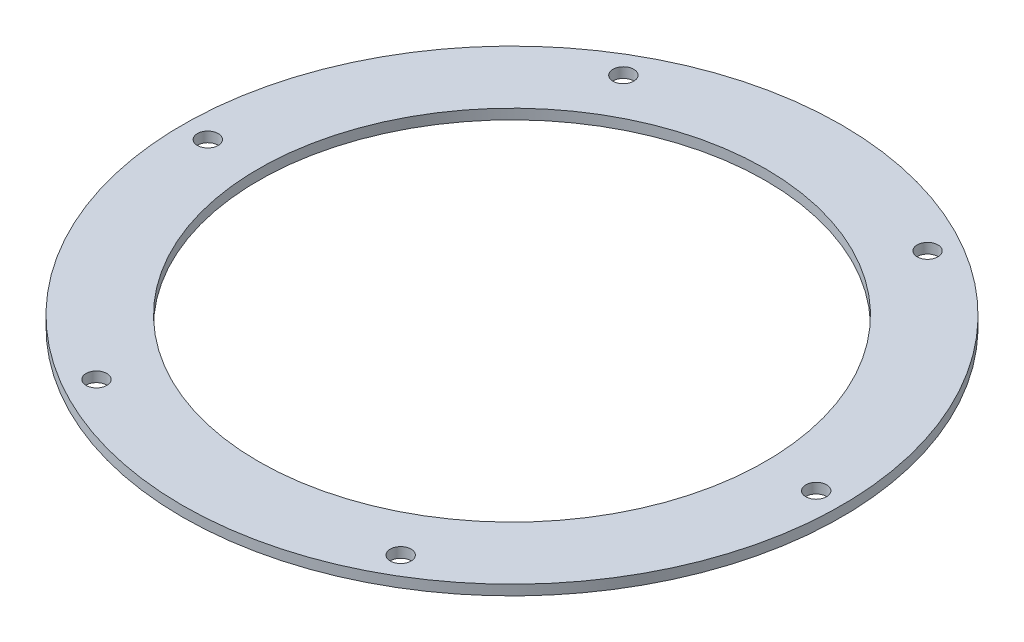
SolidWorks part; units mm, degrees
ref_plane "前视基准面" through (0, 0, 0) normal (0, 0, 1) x (1, 0, 0)
ref_plane "上视基准面" through (0, 0, 0) normal (0, 1, 0) x (1, 0, 0)
ref_plane "右视基准面" through (0, 0, 0) normal (1, 0, 0) x (0, 0, -1)
sketch "草图1" plane through (0, 0, 0) normal (0, 1, 0) x (1, 0, 0)
  circle A0 centre (0, 0) radius 50
  circle A1 centre (0, 0) radius 65
  circle A2 centre (60, 0) radius 2.05
  circle A3 centre (30, -51.9615) radius 2.05
  circle A4 centre (-30, -51.9615) radius 2.05
  circle A5 centre (-60, 0) radius 2.05
  circle A6 centre (-30, 51.9615) radius 2.05
  circle A7 centre (30, 51.9615) radius 2.05
  point P18 (0, 0)
  dimension "D1" = 100
  dimension "D2" = 130
  dimension "D4" = 6
  dimension "D5" = 4.1
  dimension "D3" = 60
extrude "凸台-拉伸1" add sketch "草图1" along normal blind 2
